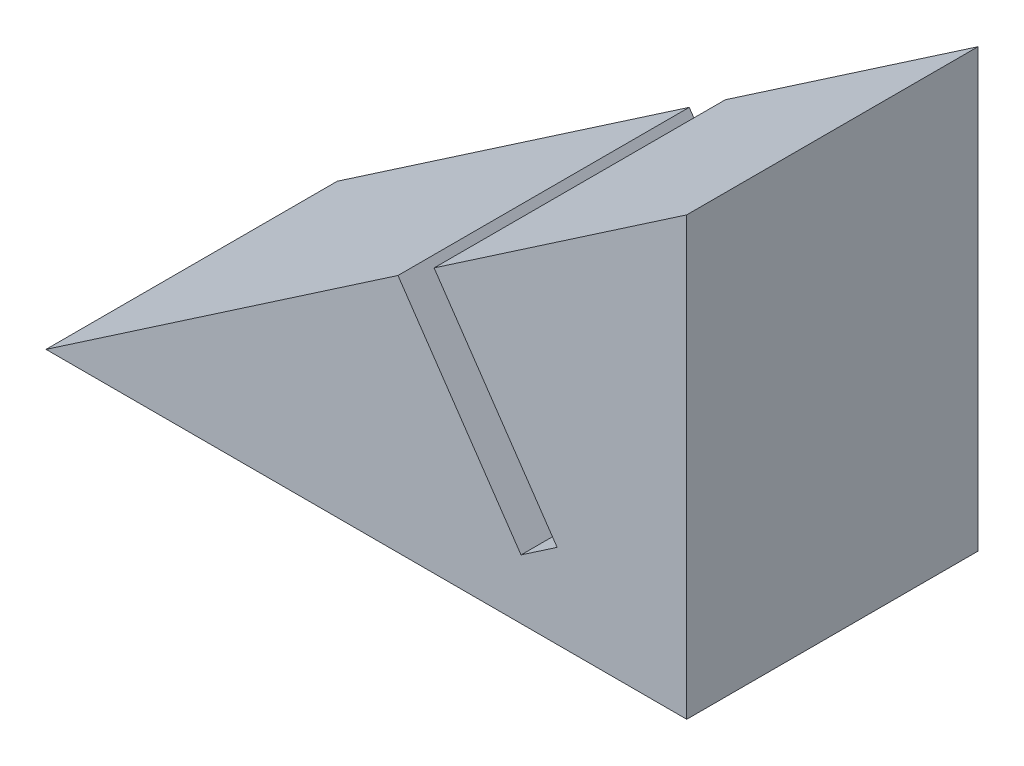
SolidWorks part; units mm, degrees
ref_plane "Plano frontal" through (0, 0, 0) normal (0, 0, 1) x (1, 0, 0)
ref_plane "Plano superior" through (0, 0, 0) normal (0, 1, 0) x (1, 0, 0)
ref_plane "Plano direito" through (0, 0, 0) normal (1, 0, 0) x (0, 0, -1)
sketch "Esboço1" plane through (0, 0, 0) normal (0, 0, 1) x (1, 0, 0)
  line L0 (0, 0) -> (0, 15)
  line L1 (0, 15) -> (-8.6754, 9.085)
  line L2 (-22, 0) -> (0, 0)
  line L3 (-8.6754, 9.085) -> (-4.4504, 2.8883)
  line L4 (-4.4504, 2.8883) -> (-5.6897, 2.0433)
  line L5 (-5.6897, 2.0433) -> (-9.9147, 8.24)
  line L6 (-9.9147, 8.24) -> (-22, 0)
  point P6 (0, 0)
  dimension "D1" = 15
  dimension "D2" = 22
  dimension "D3" = 1.5
  dimension "D4" = 7.5
  dimension "D5" = 10.5
extrude "Ressalto-extrusão1" add sketch "Esboço1" along normal blind 10
